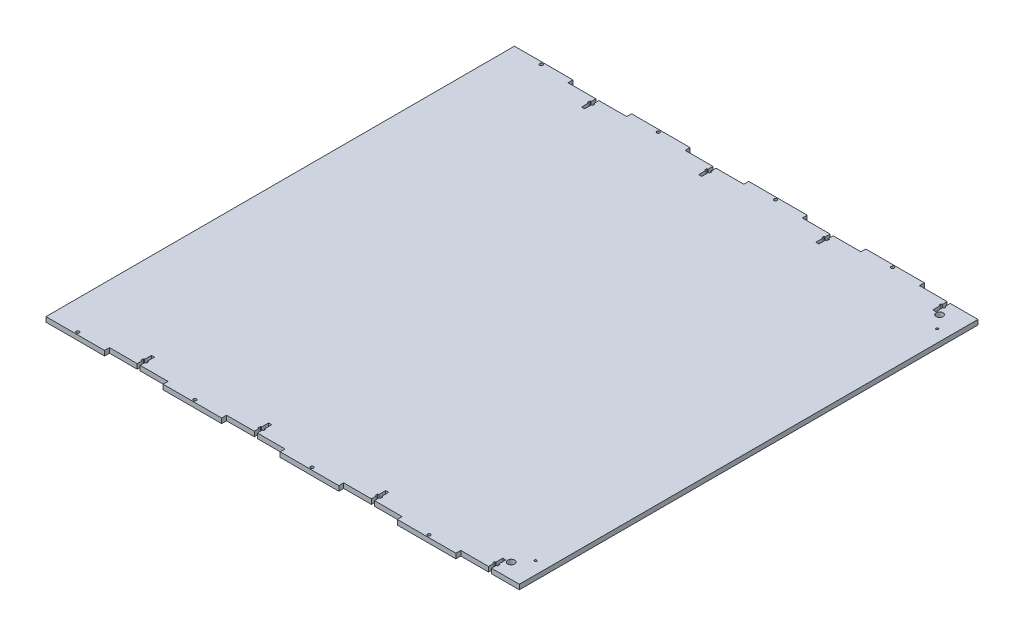
SolidWorks part; units mm, degrees
material "Acrylic (Medium-high impact)"
ref_plane "Front Plane" through (0, 0, 0) normal (0, 0, 1) x (1, 0, 0)
ref_plane "Top Plane" through (0, 0, 0) normal (0, 1, 0) x (1, 0, 0)
ref_plane "Right Plane" through (0, 0, 0) normal (1, 0, 0) x (0, 0, -1)
sketch "Sketch1" plane through (0, 0, 0) normal (0, 1, 0) x (1, 0, 0)
  line L0 (-304.8, 0) -> (304.8, 0)
  line L1 (-304.8, -304.8) -> (304.8, -304.8)
  line L2 (-304.8, -304.8) -> (-304.8, 304.8)
  line L3 (-304.8, 304.8) -> (304.8, 304.8)
  line L4 (304.8, -304.8) -> (304.8, 304.8)
  line L5 (-304.8, -304.8) -> (304.8, 304.8) construction
  line L6 (-304.8, 304.8) -> (304.8, -304.8) construction
  point P0 (0, 0)
  dimension "D1" = 609.6
  dimension "D2" = 609.6
extrude "Boss-Extrude1" add sketch "Sketch1" along normal mid plane 6.35 contours L1 L4 L0 L2
sketch "Sketch2" plane through (0, 3.175, 0) normal (0, 1, 0) x (1, 0, 0)
  line L2 (304.8, -304.8) -> (304.8, 0) construction
  line L10 (-228.6, -304.8) -> (-152.4, -304.8)
  line L11 (-228.6, -304.8) -> (-228.6, -298.45)
  line L12 (-228.6, -298.45) -> (-152.4, -298.45)
  line L13 (-152.4, -304.8) -> (-152.4, -298.45)
  line L14 (-304.8, -304.8) -> (304.8, -304.8) construction
  line L15 (-76.2, -304.8) -> (0, -304.8)
  line L16 (-76.2, -304.8) -> (-76.2, -298.45)
  line L17 (-76.2, -298.45) -> (0, -298.45)
  line L18 (0, -304.8) -> (0, -298.45)
  line L19 (-304.8, -304.8) -> (-304.8, 0) construction
  line L20 (76.2, -304.8) -> (152.4, -304.8)
  line L21 (76.2, -304.8) -> (76.2, -298.45)
  line L22 (76.2, -298.45) -> (152.4, -298.45)
  line L23 (152.4, -304.8) -> (152.4, -298.45)
  line L24 (228.6, -304.8) -> (304.8, -304.8)
  line L25 (228.6, -304.8) -> (228.6, -298.45)
  line L26 (228.6, -298.45) -> (304.8, -298.45)
  line L27 (304.8, -304.8) -> (304.8, -298.45)
  line L28 (-192.5, -298.45) -> (-192.5, -292.05)
  line L29 (-192.5, -292.05) -> (-193.89, -292.05)
  line L30 (-193.89, -292.05) -> (-193.89, -288.85)
  line L31 (-193.89, -288.85) -> (-192.5, -288.85)
  line L32 (-192.5, -288.85) -> (-192.5, -279.8)
  line L33 (-192.5, -279.8) -> (-188.5, -279.8)
  line L34 (-188.5, -279.8) -> (-188.5, -288.85)
  line L35 (-188.5, -288.85) -> (-187.11, -288.85)
  line L36 (-187.11, -288.85) -> (-187.11, -292.05)
  line L37 (-187.11, -292.05) -> (-188.5, -292.05)
  line L38 (-188.5, -292.05) -> (-188.5, -298.45)
  line L39 (-190.5, -279.8) -> (-190.5, -298.45) construction
  line L40 (-40.1, -292.05) -> (-41.49, -292.05)
  line L41 (-41.49, -292.05) -> (-41.49, -288.85)
  line L42 (-41.49, -288.85) -> (-40.1, -288.85)
  line L43 (-40.1, -288.85) -> (-40.1, -279.8)
  line L44 (-40.1, -279.8) -> (-36.1, -279.8)
  line L45 (-36.1, -279.8) -> (-36.1, -288.85)
  line L46 (-36.1, -288.85) -> (-34.71, -288.85)
  line L47 (-34.71, -288.85) -> (-34.71, -292.05)
  line L48 (-34.71, -292.05) -> (-36.1, -292.05)
  line L49 (-40.1, -298.45) -> (-40.1, -292.05)
  line L50 (-36.1, -292.05) -> (-36.1, -298.45)
  line L51 (-38.1, -279.8) -> (-38.1, -298.45) construction
  line L52 (112.3, -292.05) -> (110.91, -292.05)
  line L53 (110.91, -292.05) -> (110.91, -288.85)
  line L54 (110.91, -288.85) -> (112.3, -288.85)
  line L55 (112.3, -288.85) -> (112.3, -279.8)
  line L56 (112.3, -279.8) -> (116.3, -279.8)
  line L57 (116.3, -279.8) -> (116.3, -288.85)
  line L58 (116.3, -288.85) -> (117.69, -288.85)
  line L59 (117.69, -288.85) -> (117.69, -292.05)
  line L60 (117.69, -292.05) -> (116.3, -292.05)
  line L61 (112.3, -298.45) -> (112.3, -292.05)
  line L62 (116.3, -292.05) -> (116.3, -298.45)
  line L63 (114.3, -279.8) -> (114.3, -298.45) construction
  line L64 (264.7, -292.05) -> (263.31, -292.05)
  line L65 (263.31, -292.05) -> (263.31, -288.85)
  line L66 (263.31, -288.85) -> (264.7, -288.85)
  line L67 (264.7, -288.85) -> (264.7, -279.8)
  line L68 (264.7, -279.8) -> (268.7, -279.8)
  line L69 (268.7, -279.8) -> (268.7, -288.85)
  line L70 (268.7, -288.85) -> (270.09, -288.85)
  line L71 (270.09, -288.85) -> (270.09, -292.05)
  line L72 (270.09, -292.05) -> (268.7, -292.05)
  line L73 (264.7, -298.45) -> (264.7, -292.05)
  line L74 (268.7, -292.05) -> (268.7, -298.45)
  line L75 (266.7, -279.8) -> (266.7, -298.45) construction
  line L76 (304.8, -304.8) -> (304.8, 0) construction
  circle A0 centre (-266.7, -301.625) radius 2
  circle A1 centre (-114.3, -301.625) radius 2
  circle A2 centre (38.1, -301.625) radius 2
  circle A3 centre (190.5, -301.625) radius 2
  circle A4 centre (274.46, -278.775) radius 4.5
  circle A5 centre (288.8, -261.3) radius 1.5
  point P22 (-76.2, -301.625)
  line M22 (-304.8, -304.8) -> (304.8, -304.8)
  line M23 (304.8, -304.8) -> (304.8, 0)
  dimension "D10" = 4
  dimension "D19" = 9
  dimension "D22" = 16
  dimension "D24" = 3
  dimension "D1" = 76.2
  dimension "D2" = 76.2
  dimension "D3" = 76.2
  dimension "D4" = 76.2
  dimension "D5" = 76.2
  dimension "D6" = 76.2
  dimension "D7" = 76.2
  dimension "D8" = 6.35
  dimension "D9" = 76.2
  dimension "D11" = 3.175
  dimension "D12" = 38.1
  dimension "D13" = 4
  dimension "D14" = 6.78
  dimension "D15" = 3.2
  dimension "D16" = 6.4
  dimension "D17" = 18.65
  dimension "D18" = 38.1
  dimension "D20" = 19.675
  dimension "D21" = 30.34
  dimension "D23" = 43.5
extrude "Cut-Extrude1" cut sketch "Sketch2" along direction (0, 1, 0) on the side against the normal through all both and the other way through all contours A0 | L13 L12 L11 M22 | L38 L37 L36 L35 L34 L33 L32 L31 L30 L29 L28 L12 | A1 | L18 L17 L16 M22 | L50 L48 L47 L46 L45 L44 L43 L42 L41 L40 L49 L17 | A2 | L23 L22 L21 M22 | L62 L60 L59 L58 L57 L56 L55 L54 L53 L52 L61 L22 | A3 | L26 L25 M22 M23 | L74 L72 L71 L70 L69 L68 L67 L66 L65 L64 L73 L26 | A4 | A5
mirror "Mirror1" about plane through (0, 3.175, 0) normal (0, 0, -1) of "Cut-Extrude1", "Boss-Extrude1"
